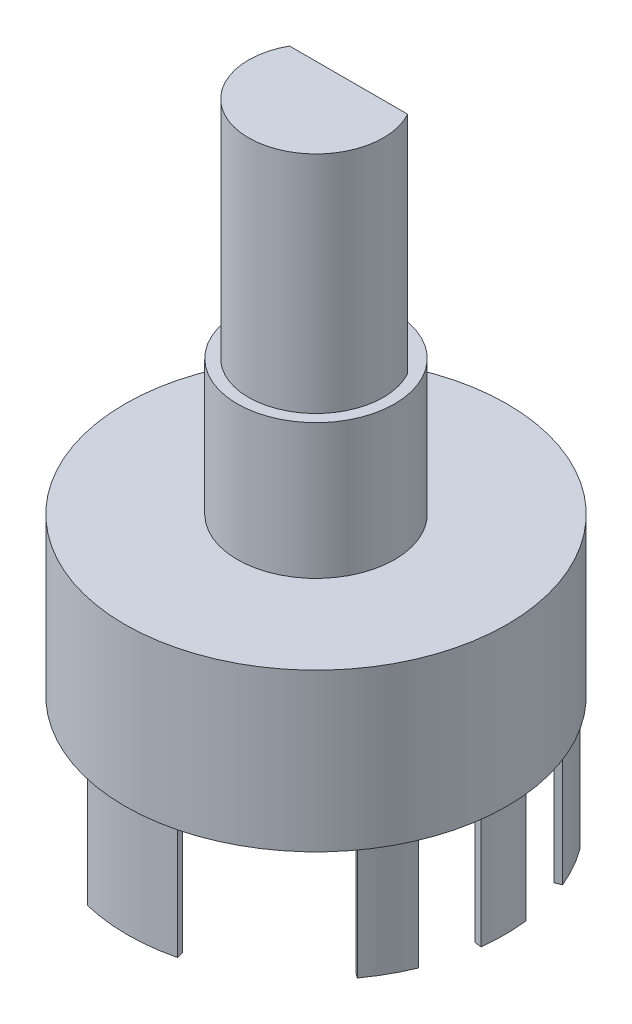
SolidWorks part; units mm, degrees
ref_plane "Front Plane" through (0, 0, 0) normal (0, 0, 1) x (1, 0, 0)
ref_plane "Top Plane" through (0, 0, 0) normal (0, 1, 0) x (1, 0, 0)
ref_plane "Right Plane" through (0, 0, 0) normal (1, 0, 0) x (0, 0, -1)
sketch "Sketch2" plane through (0, 0, 0) normal (0, 0, 1) x (1, 0, 0)
  line L0 (0, -1000) -> (0, 49000) construction
  line L1 (0, 0) -> (8.5, 0)
  line L2 (8.5, 0) -> (8.5, 7)
  line L3 (8.5, 7) -> (3.5, 7)
  line L4 (3.5, 7) -> (3.5, 13)
  line L5 (3.5, 13) -> (3, 13)
  line L6 (3, 13) -> (3, 23)
  line L7 (3, 23) -> (0, 23)
  line L8 (0, 23) -> (0, 0)
  dimension "D1" = 7
  dimension "D2" = 17
  dimension "D3" = 7
  dimension "D4" = 6
  dimension "D5" = 10
  dimension "D6" = 6
revolve "Revolve1" add sketch "Sketch2" angle 360 about L0
sketch "Sketch3" plane through (0, 0, 0) normal (0, -1, 0) x (1, 0, 0)
  line L0 (6.5442, 4.7732) -> (6.7866, 4.95)
  line L1 (7.4871, 3.0909) -> (7.7644, 3.2053)
  line L2 (8.0424, 0.9643) -> (8.3403, 1)
  line L3 (8.0424, -0.9643) -> (8.3403, -1)
  line L4 (7.4871, -3.0909) -> (7.7644, -3.2053)
  line L5 (6.5442, -4.7732) -> (6.7866, -4.95)
  line L6 (8.3403, 1) -> (8.3403, -1) construction
  line L7 (6.7866, 4.95) -> (7.7644, 3.2053) construction
  line L8 (6.7866, -4.95) -> (7.7644, -3.2053) construction
  line L9 (-1.9286, -7.8671) -> (-2, -8.1584)
  line L11 (2, -8.1584) -> (1.9286, -7.8671)
  line L12 (-1.9286, 7.8671) -> (-2, 8.1584)
  line L14 (2, 8.1584) -> (1.9286, 7.8671)
  arc A3 (-1.9286, -7.8671) -> (1.9286, -7.8671) centre (0, 0) ccw
  arc A4 (-2, -8.1584) -> (2, -8.1584) centre (0, 0) ccw
  circle A5 centre (0, 0) radius 8.5 construction
  arc A6 (1.9286, 7.8671) -> (-1.9286, 7.8671) centre (0, 0) ccw
  arc A7 (2, 8.1584) -> (-2, 8.1584) centre (0, 0) ccw
  arc A8 (6.5442, -4.7732) -> (7.4871, -3.0909) centre (0, 0) ccw
  arc A9 (6.7866, -4.95) -> (7.7644, -3.2053) centre (0, 0) ccw
  arc A10 (7.4871, 3.0909) -> (6.5442, 4.7732) centre (0, 0) ccw
  arc A11 (7.7644, 3.2053) -> (6.7866, 4.95) centre (0, 0) ccw
  arc A12 (8.0424, -0.9643) -> (8.0424, 0.9643) centre (0, 0) ccw
  arc A13 (8.3403, -1) -> (8.3403, 1) centre (0, 0) ccw
  point P12 (0, 0)
  point P17 (0, 0)
  point P26 (1.9331, 8.138)
  point P27 (0, 0)
  point P28 (0, 0)
  point P29 (0, 0)
  point P30 (0, 0)
  point P31 (0, 0)
  point P32 (0, 0)
  point P33 (0, 0)
  point P34 (0, 0)
  point P35 (0, 0)
  point P36 (7.8753, 3.1984)
  point P37 (6.5848, 4.7171)
  point P38 (0, 0)
  point P39 (0, 0)
  point P40 (8.2451, -0.9753)
  dimension "D1" = 2
  dimension "D3" = 0.4
  dimension "D5" = 0.1
  dimension "D6" = 0.1
  dimension "D2" = 9.9
  dimension "D4" = 4
extrude "Boss-Extrude1" add sketch "Sketch3" along normal blind 5
sketch "Sketch4" plane through (0, 0, 0) normal (1, 0, 0) x (0, 0, -1)
  line L0 (3, 23) -> (-3, 23) construction
  line L1 (1.45, 23) -> (3, 23)
  line L2 (1.45, 23) -> (1.45, 13)
  line L3 (1.45, 13) -> (3, 13)
  line L4 (3, 23) -> (3, 13)
  line L5 (-3, 23) -> (-3, 13) construction
  dimension "D1" = 4.45
extrude "Cut-Extrude1" cut sketch "Sketch4" against normal through all both and the other way through all
